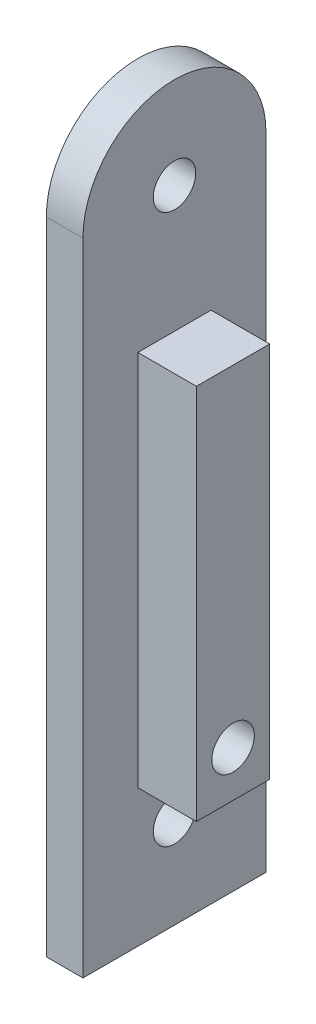
SolidWorks part; units mm, degrees
ref_plane "Front Plane" through (0, 0, 0) normal (0, 0, 1) x (1, 0, 0)
ref_plane "Top Plane" through (0, 0, 0) normal (0, 1, 0) x (1, 0, 0)
ref_plane "Right Plane" through (0, 0, 0) normal (1, 0, 0) x (0, 0, -1)
sketch "Sketch1" plane through (0, 0, 0) normal (1, 0, 0) x (0, 0, -1)
  line L0 (-6.35, 0) -> (-6.35, -44.45)
  line L1 (-6.35, -44.45) -> (6.35, -44.45)
  line L2 (6.35, -44.45) -> (6.35, 0)
  line L3 (-6.35, -44.45) -> (6.35, -44.45) construction
  arc A0 (-6.35, 0) -> (6.35, 0) centre (0, 0) cw
  arc A1 (6.35, 0) -> (-6.35, 0) centre (0, 0) ccw construction
extrude "Boss-Extrude1" add sketch "Sketch1" along normal blind 2.54
sketch "Sketch2" plane through (2.54, 0, 0) normal (1, 0, 0) x (0, 0, -1)
  line L0 (-2.54, -34.925) -> (-2.54, -8.7723)
  line L1 (-2.54, -8.7723) -> (2.54, -8.7723)
  line L2 (2.54, -8.7723) -> (2.54, -34.925)
  line L3 (2.54, -34.925) -> (-2.54, -34.925)
  line L4 (-2.54, -21.8486) -> (-6.35, -21.8486) construction
  line L5 (-6.35, 0) -> (-6.35, -44.45) construction
  line L6 (2.54, -21.8486) -> (6.35, -21.8486) construction
  line L7 (6.35, -44.45) -> (6.35, 0) construction
  line L8 (0, -8.7723) -> (0, -3.6923) construction
  line L9 (0.3452, -3.6923) -> (-0.3452, -3.6923) construction
  line L10 (0, -34.925) -> (0, -44.45) construction
  line L11 (-6.35, -44.45) -> (6.35, -44.45) construction
  dimension "D1" = 9.525
  dimension ".3" = 5.08
  dimension "D2" = 3.81
extrude "Boss-Extrude2" add sketch "Sketch2" along normal up to surface (4.064 mm away)
sketch "Sketch3" plane through (0, 0, 0) normal (-1, 0, 0) x (0, 0, 1)
  circle A0 centre (0, 0) radius 1.4732
  circle A1 centre (0, 0) radius 1.4732 construction
extrude "Cut-Extrude1" cut sketch "Sketch3" against normal through all both and the other way through all
sketch "Sketch4" plane through (0, 0, 0) normal (-1, 0, 0) x (0, 0, 1)
  line L0 (0, 0) -> (0, -31.75)
  line L1 (0, -31.75) -> (0, -38.1)
  dimension "D1" = 31.75
  dimension "D2" = 6.35
hole_wizard "#4 Clearance Hole1" positions "Sketch5" profile "Sketch6" hole size "#4" standard "ANSI Inch" end condition through all
sketch "Sketch5" plane through (0, 0, 0) normal (-1, 0, 0) x (0, 0, 1)
  point P0 (0, -31.75)
  point P3 (0, -38.1)
sketch "Sketch6" plane through (0, -31.75, 0) normal (0, 1, 0) x (0, 0, 1)
  line L0 (0, 0) -> (0, 6.604)
  line L1 (0, 6.604) -> (1.4732, 6.604)
  line L2 (1.4732, 6.604) -> (1.4732, 0)
  line L5 (1.4732, 0) -> (0, 0)
  line L11 (0, -6.35) -> (0, 107.95) construction
  dimension "Thru Hole Dia." = 2.9464
  dimension "Thru Hole Depth" = 6.604
